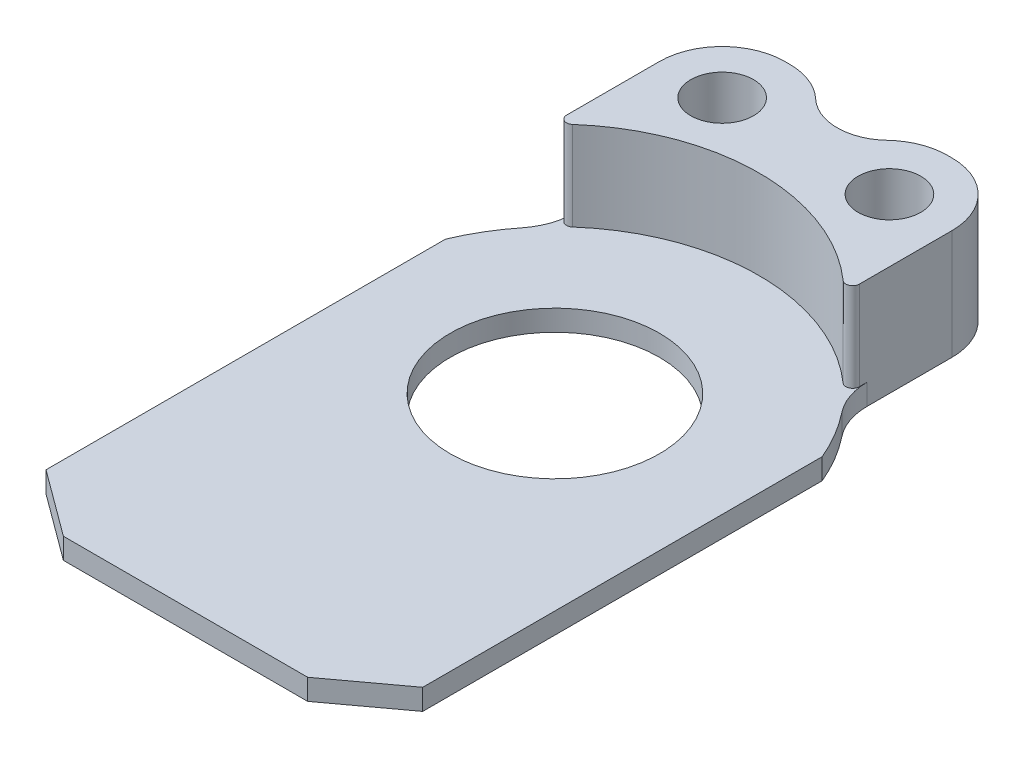
SolidWorks part; units mm, degrees
ref_plane "Front Plane" through (0, 0, 0) normal (0, 0, 1) x (1, 0, 0)
ref_plane "Top Plane" through (0, 0, 0) normal (0, 1, 0) x (1, 0, 0)
ref_plane "Right Plane" through (0, 0, 0) normal (1, 0, 0) x (0, 0, -1)
sketch "Sketch1" plane through (0, 0, 0) normal (0, 1, 0) x (1, 0, 0)
  line L1 (-14.3002, -24.3332) -> (-9.271, -28.0416)
  line L2 (-9.271, -28.0416) -> (9.271, -28.0416)
  line L3 (9.271, -28.0416) -> (14.3002, -24.3332)
  line L4 (14.3002, -24.3332) -> (14.3002, 5.9944)
  line L5 (-14.3002, 5.9944) -> (-14.3002, -24.3332)
  circle A0 centre (0, 0) radius 7.9375
  arc A2 (-14.3002, 5.9944) -> (14.3002, 5.9944) centre (0, 0) cw
  dimension "D1" = 15.875
  dimension "D2" = 28.0416
  dimension "D3" = 14.3002
  dimension "D5" = 5.0292
  dimension "D6" = 5.0292
  dimension "D7" = 3.7084
  dimension "D8" = 3.7084
  dimension "D9" = 34.036
  dimension "D10" = 34.036
extrude "Boss-Extrude1" add sketch "Sketch1" along normal blind 1.5875
sketch "Sketch2" plane through (0, 0, 0) normal (0, -1, 0) x (1, 0, 0)
  line L0 (-11.1125, -19.05) -> (-11.1125, -12.6011)
  line L1 (11.1125, -19.05) -> (11.1125, -12.6011)
  line L2 (-6.35, -23.8125) -> (-5.9834, -23.8125)
  line L3 (14.3002, 24.3332) -> (14.3002, -5.9944) construction
  line L4 (6.35, -23.8125) -> (5.9834, -23.8125)
  circle A0 centre (-6.35, -19.05) radius 2.3813
  circle A1 centre (6.35, -19.05) radius 2.3813
  arc A3 (-14.3002, -5.9944) -> (-12.1448, -9.6401) centre (0, 0) ccw
  arc A4 (-11.1125, -12.6011) -> (-12.1448, -9.6401) centre (-15.875, -12.6011) ccw
  arc A5 (12.1448, -9.6401) -> (14.3002, -5.9944) centre (0, 0) ccw
  arc A6 (12.1448, -9.6401) -> (11.1125, -12.6011) centre (15.875, -12.6011) ccw
  arc A7 (11.1125, -19.05) -> (6.35, -23.8125) centre (6.35, -19.05) cw
  arc A8 (-6.35, -23.8125) -> (-11.1125, -19.05) centre (-6.35, -19.05) cw
  arc A10 (-2.7174, -22.5162) -> (-5.9834, -23.8125) centre (-5.9834, -19.05) cw
  arc A11 (-2.7174, -22.5162) -> (2.7174, -22.5162) centre (0, -25.4) cw
  arc A12 (2.7174, -22.5162) -> (5.9834, -23.8125) centre (5.9834, -19.05) ccw
  arc M7 (-14.3002, -5.9944) -> (14.3002, -5.9944) centre (0, 0) ccw
  dimension "D5" = 4.7625
  dimension "D6" = 4.7625
  dimension "D10" = 4.7625
  dimension "D11" = 4.7625
  dimension "D12" = 4.7625
  dimension "D14" = 4.7625
  dimension "D15" = 4.7625
  dimension "D1" = 19.05
  dimension "D2" = 19.05
  dimension "D3" = 6.35
  dimension "D4" = 6.35
  dimension "D7" = 4.7625
  dimension "D8" = 4.7625
  dimension "D9" = 4.7625
  dimension "D13" = 25.4
extrude "Boss-Extrude2" add sketch "Sketch2" against normal blind 8.3344 contours A11 A12 L4 A7 L1 A6 A4 L0 A8 L2 A10 A0 A1 M7
sketch "Sketch3" plane through (0, 8.3344, 0) normal (0, 1, 0) x (1, 0, 0)
  line L0 (-11.1125, 19.05) -> (-11.1125, 11.9994)
  line L1 (11.1125, 19.05) -> (11.1125, 11.9994)
  line L2 (-11.1125, 19.05) -> (-16.621, 6.8904)
  line L3 (-16.621, 6.8904) -> (16.4162, 6.3503)
  line L4 (16.4162, 6.3503) -> (11.1125, 19.05)
  arc A0 (12.1448, 9.6401) -> (-12.1448, 9.6401) centre (0, 0) ccw construction
  arc A1 (10.2681, 11.6187) -> (-10.2681, 11.6187) centre (0, 0) ccw
  arc A2 (11.1125, 11.9994) -> (10.2681, 11.6187) centre (10.6045, 11.9994) cw
  arc A3 (-11.1125, 11.9994) -> (-10.2681, 11.6187) centre (-10.6045, 11.9994) ccw
  point P12 (11.1125, 10.8139)
  point P15 (-11.1125, 10.8139)
  dimension "D1" = 0.508
extrude "Cut-Extrude1" cut sketch "Sketch3" against normal blind 6.7469
